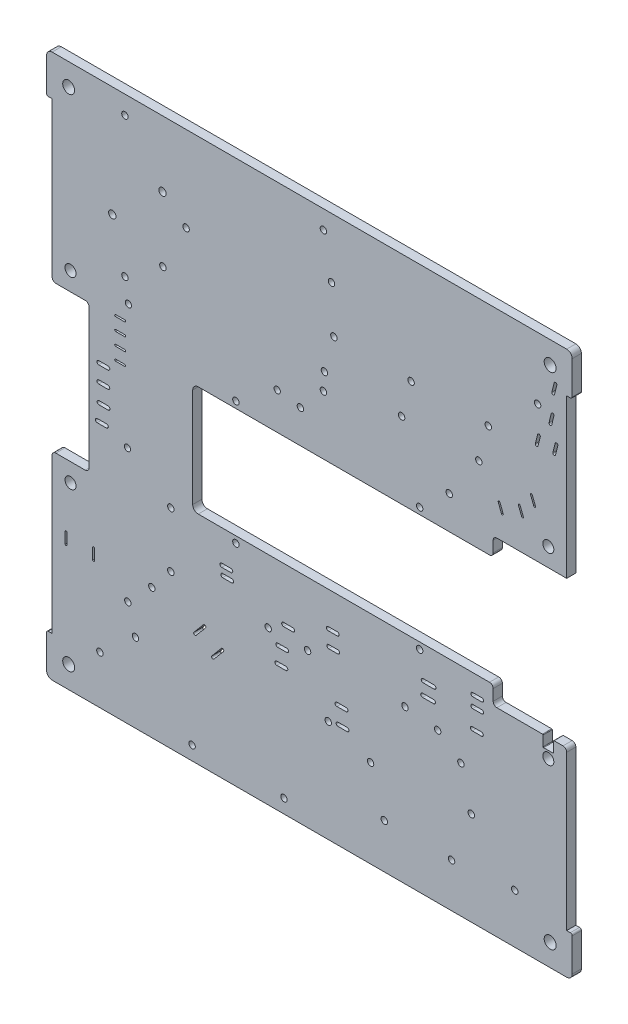
SolidWorks part; units mm, degrees
ref_plane "Front Plane" through (0, 0, 0) normal (0, 0, 1) x (1, 0, 0)
ref_plane "Top Plane" through (0, 0, 0) normal (0, 1, 0) x (1, 0, 0)
ref_plane "Right Plane" through (0, 0, 0) normal (1, 0, 0) x (0, 0, -1)
sketch "Sketch1" plane through (0, 0, 0) normal (0, 0, 1) x (1, 0, 0)
  line L0 (0, -204.8237) -> (0, 174.4772) construction
  line L1 (-143, 174.4772) -> (-143, 126) construction
  line L2 (-199.587, 148) -> (272.3491, 148) construction
  line L3 (-199.587, -148) -> (272.3491, -148) construction
  line L4 (143, 174.4772) -> (143, 127) construction
  line L5 (-199.587, 39.9718) -> (272.3491, 39.9718) construction
  line L6 (-60.5, 29.9898) -> (98, 29.9898)
  line L9 (-63.5, -26.9693) -> (-63.5, 26.9898)
  line L10 (-199.587, 0) -> (272.3491, 0) construction
  line L11 (-60.5, -29.9693) -> (98, -29.9693)
  line L12 (143, -127) -> (143, -204.8237) construction
  line L13 (-199.587, 126) -> (272.3491, 126) construction
  line L14 (-140, 126) -> (-142, 126)
  line L15 (-140, 126) -> (-140, 41.9718)
  line L16 (-143, -127) -> (-143, -145)
  line L17 (-143, -126) -> (-143, -204.8237) construction
  line L18 (-140, -126) -> (-142, -126)
  line L19 (140, -126) -> (142, -126)
  line L20 (140, 126) -> (140, 39.9718)
  line L21 (140, 126) -> (142, 126)
  line L22 (140, -41.9718) -> (140, -126)
  line L23 (143, 127) -> (143, 145)
  line L24 (-132.4113, -74.3153) -> (-132.4113, -80.3153) construction
  line L25 (102, -39.9718) -> (126.8607, -39.9718)
  line L26 (100, -37.9718) -> (100, -31.9693)
  line L27 (100, 37.9718) -> (100, 31.9898)
  line L28 (102, 39.9718) -> (140, 39.9718)
  line L29 (-138, 39.9718) -> (-121.9403, 39.9718)
  line L30 (-119.9403, 37.9718) -> (-119.9403, -38)
  line L31 (-121.9403, -40) -> (-138, -40)
  line L37 (-143, 145) -> (-143, 127)
  line L38 (-140, -148) -> (140, -148)
  line L41 (143, -145) -> (143, -127)
  line L46 (140, 148) -> (-140, 148)
  line L48 (-140, -42) -> (-140, -126)
  line L49 (-131.9113, -74.3153) -> (-131.9113, -80.3153)
  line L50 (-132.9113, -74.3153) -> (-132.9113, -80.3153)
  line L51 (-117.4113, -74.3153) -> (-117.4113, -80.3153) construction
  line L52 (-116.9113, -74.3153) -> (-116.9113, -80.3153)
  line L53 (-117.9113, -74.3153) -> (-117.9113, -80.3153)
  line L66 (-105.4366, 41.087) -> (-100.4366, 41.087) construction
  line L67 (-105.4366, 41.587) -> (-100.4366, 41.587)
  line L68 (-105.4366, 40.587) -> (-100.4366, 40.587)
  line L69 (-105.4366, 34.087) -> (-100.4366, 34.087) construction
  line L70 (-105.4366, 34.587) -> (-100.4366, 34.587)
  line L71 (-105.4366, 33.587) -> (-100.4366, 33.587)
  line L72 (-105.4366, 27.087) -> (-100.4366, 27.087) construction
  line L73 (-105.4366, 27.587) -> (-100.4366, 27.587)
  line L74 (-105.4366, 26.587) -> (-100.4366, 26.587)
  line L75 (-105.4366, 20.087) -> (-100.4366, 20.087) construction
  line L76 (-105.4366, 20.587) -> (-100.4366, 20.587)
  line L77 (-105.4366, 19.587) -> (-100.4366, 19.587)
  line L96 (-57.0801, -81.1454) -> (-62.234, -87.264) construction
  line L97 (-56.5065, -81.6286) -> (-61.6604, -87.7472)
  line L98 (-57.6538, -80.6623) -> (-62.8077, -86.7809)
  line L99 (-52.51, -93.5704) -> (-47.3561, -87.4518) construction
  line L100 (-53.0836, -93.0872) -> (-47.9297, -86.9686)
  line L101 (-51.9364, -94.0536) -> (-46.7825, -87.935)
  line L102 (-199.587, 28.9898) -> (272.3491, 28.9898) construction
  line L103 (-199.587, -28.9693) -> (272.3491, -28.9693) construction
  line L110 (132.8393, -45.8) -> (132.8393, -40.2718)
  line L111 (133.1393, -39.9718) -> (138, -39.9718)
  line L113 (132.5393, -46.1) -> (127.4607, -46.1)
  line L116 (127.1607, -45.8) -> (127.1607, -40.2718)
  line L120 (-199.587, 174.4772) -> (-199.587, -204.8237) construction
  line L121 (-199.587, -204.8237) -> (272.3491, -204.8237) construction
  line L122 (272.3491, -204.8237) -> (272.3491, 174.4772) construction
  line L123 (-199.587, 174.4772) -> (272.3491, 174.4772) construction
  line L157 (-114.6311, 14.3002) -> (-109.6311, 14.3002) construction
  line L158 (-114.6311, 15.3002) -> (-109.6311, 15.3002)
  line L159 (-114.6311, 13.3002) -> (-109.6311, 13.3002)
  line L160 (-114.6311, 5.2497) -> (-109.6311, 5.2497) construction
  line L161 (-114.6311, 6.2497) -> (-109.6311, 6.2497)
  line L162 (-114.6311, 4.2497) -> (-109.6311, 4.2497)
  line L163 (-114.4929, -4.4876) -> (-109.4929, -4.4876) construction
  line L164 (-114.4929, -3.4876) -> (-109.4929, -3.4876)
  line L165 (-114.4929, -5.4876) -> (-109.4929, -5.4876)
  line L166 (-115.4455, -13.4042) -> (-110.4455, -13.4042) construction
  line L167 (-115.4455, -12.4042) -> (-110.4455, -12.4042)
  line L168 (-115.4455, -14.4042) -> (-110.4455, -14.4042)
  line L169 (-14.0645, -58.778) -> (-9.0645, -58.778) construction
  line L170 (-14.0645, -57.778) -> (-9.0645, -57.778)
  line L171 (-14.0645, -59.778) -> (-9.0645, -59.778)
  line L172 (10.4507, -56.9364) -> (15.4507, -56.9364) construction
  line L173 (10.4507, -55.9364) -> (15.4507, -55.9364)
  line L174 (10.4507, -57.9364) -> (15.4507, -57.9364)
  line L175 (-47.7039, -47.6687) -> (-42.7039, -47.6687) construction
  line L176 (-47.7039, -46.6687) -> (-42.7039, -46.6687)
  line L177 (-47.7039, -48.6687) -> (-42.7039, -48.6687)
  line L178 (-47.2405, -52.3025) -> (-42.2405, -52.3025) construction
  line L179 (-47.2405, -51.3025) -> (-42.2405, -51.3025)
  line L180 (-47.2405, -53.3025) -> (-42.2405, -53.3025)
  line L181 (10.219, -48.5955) -> (15.219, -48.5955) construction
  line L182 (10.219, -47.5955) -> (15.219, -47.5955)
  line L183 (10.219, -49.5955) -> (15.219, -49.5955)
  line L184 (-17.3117, -70.106) -> (-12.3117, -70.106) construction
  line L185 (-17.3117, -69.106) -> (-12.3117, -69.106)
  line L186 (-17.3117, -71.106) -> (-12.3117, -71.106)
  line L187 (-17.7732, -78.875) -> (-12.7732, -78.875) construction
  line L188 (-17.7732, -77.875) -> (-12.7732, -77.875)
  line L189 (-17.7732, -79.875) -> (-12.7732, -79.875)
  line L190 (88.8087, -40.369) -> (93.8087, -40.369) construction
  line L191 (88.8087, -39.369) -> (93.8087, -39.369)
  line L192 (88.8087, -41.369) -> (93.8087, -41.369)
  line L193 (88.8087, -46.0036) -> (93.8087, -46.0036) construction
  line L194 (88.8087, -45.0036) -> (93.8087, -45.0036)
  line L195 (88.8087, -47.0036) -> (93.8087, -47.0036)
  line L196 (88.6354, -56.5792) -> (93.6354, -56.5792) construction
  line L197 (88.6354, -55.5792) -> (93.6354, -55.5792)
  line L198 (88.6354, -57.5792) -> (93.6354, -57.5792)
  line L199 (114.1692, 61.6198) -> (115.9798, 56.9591) construction
  line L200 (114.6353, 61.8008) -> (116.4459, 57.1402)
  line L201 (113.7031, 61.4387) -> (115.5138, 56.7781)
  line L202 (103.189, 57.5463) -> (104.9997, 52.8856) construction
  line L203 (103.6551, 57.7273) -> (105.4657, 53.0667)
  line L204 (102.723, 57.3652) -> (104.5336, 52.7046)
  line L205 (120.7594, 69.8959) -> (122.5701, 65.2352) construction
  line L206 (121.2255, 70.077) -> (123.0361, 65.4163)
  line L207 (120.2934, 69.7148) -> (122.104, 65.0542)
  line L244 (61.85, -47.301) -> (67.85, -47.301) construction
  line L245 (61.85, -46.301) -> (67.85, -46.301)
  line L246 (61.85, -48.301) -> (67.85, -48.301)
  line L247 (61.5696, -54.313) -> (67.5696, -54.313) construction
  line L248 (61.5696, -53.313) -> (67.5696, -53.313)
  line L249 (61.5696, -55.313) -> (67.5696, -55.313)
  line L250 (131.1069, 108.3154) -> (132.3521, 113.3154) construction
  line L251 (130.3791, 108.4967) -> (131.6243, 113.4967)
  line L252 (131.8346, 108.1342) -> (133.0799, 113.1342)
  line L259 (132.6394, 123.5259) -> (133.8846, 128.5259) construction
  line L260 (131.9116, 123.7072) -> (133.1569, 128.7072)
  line L261 (133.3672, 123.3447) -> (134.6124, 128.3447)
  line L262 (123.6481, 94.7242) -> (124.8933, 99.7242) construction
  line L263 (122.9203, 94.9054) -> (124.1656, 99.9054)
  line L264 (124.3759, 94.5429) -> (125.6211, 99.5429)
  line L265 (133.2255, 95.2911) -> (134.4707, 100.2911) construction
  line L266 (132.4977, 95.4724) -> (133.743, 100.4724)
  line L267 (133.9533, 95.1099) -> (135.1985, 100.1099)
  line L286 (14.9622, -81.8846) -> (19.9622, -81.8846) construction
  line L287 (14.9622, -80.8846) -> (19.9622, -80.8846)
  line L288 (14.9622, -82.8846) -> (19.9622, -82.8846)
  line L289 (15.4975, -90.9862) -> (20.4975, -90.9862) construction
  line L290 (15.4975, -89.9862) -> (20.4975, -89.9862)
  line L291 (15.4975, -91.9862) -> (20.4975, -91.9862)
  arc A0 (-140, -148) -> (-143, -145) centre (-140, -145) cw
  arc A1 (143, 145) -> (140, 148) centre (140, 145) ccw
  arc A2 (-143, 145) -> (-140, 148) centre (-140, 145) cw
  arc A3 (143, -145) -> (140, -148) centre (140, -145) cw
  circle A4 centre (130, 50) radius 3
  circle A5 centre (130, -50) radius 3
  arc A10 (-63.5, -26.9693) -> (-60.5, -29.9693) centre (-60.5, -26.9693) ccw
  arc A11 (-63.5, 26.9898) -> (-60.5, 29.9898) centre (-60.5, 26.9898) cw
  circle A12 centre (-130, -50) radius 3
  circle A13 centre (-130, 50) radius 3
  circle A14 centre (-131, -136) radius 3.25
  circle A15 centre (131, -136) radius 3.25
  circle A16 centre (131, 136) radius 3.25
  circle A17 centre (-131, 136) radius 3.25
  arc A18 (-142, -126) -> (-143, -127) centre (-142, -127) ccw
  arc A19 (-142, 126) -> (-143, 127) centre (-142, 127) cw
  arc A27 (142, -126) -> (143, -127) centre (142, -127) cw
  arc A28 (142, 126) -> (143, 127) centre (142, 127) ccw
  arc A29 (-131.9113, -74.3153) -> (-132.9113, -74.3153) centre (-132.4113, -74.3153) ccw
  arc A30 (-132.9113, -80.3153) -> (-131.9113, -80.3153) centre (-132.4113, -80.3153) ccw
  circle A31 centre (111.7352, -121.1181) radius 1.75
  circle A32 centre (88.0893, -97) radius 1.75
  arc A33 (102, -39.9718) -> (100, -37.9718) centre (102, -37.9718) cw
  arc A34 (100, 37.9718) -> (102, 39.9718) centre (102, 37.9718) cw
  arc A35 (100, -31.9693) -> (98, -29.9693) centre (98, -31.9693) ccw
  arc A36 (100, 31.9898) -> (98, 29.9898) centre (98, 31.9898) cw
  arc A37 (138, -39.9718) -> (140, -41.9718) centre (138, -41.9718) cw
  arc A38 (-138, -40) -> (-140, -42) centre (-138, -42) ccw
  arc A39 (-138, 39.9718) -> (-140, 41.9718) centre (-138, 41.9718) cw
  arc A40 (-119.9403, -38) -> (-121.9403, -40) centre (-121.9403, -38) cw
  arc A41 (-121.9403, 39.9718) -> (-119.9403, 37.9718) centre (-121.9403, 37.9718) cw
  arc A42 (-116.9113, -74.3153) -> (-117.9113, -74.3153) centre (-117.4113, -74.3153) ccw
  arc A43 (-117.9113, -80.3153) -> (-116.9113, -80.3153) centre (-117.4113, -80.3153) ccw
  circle A46 centre (-107.2747, 87.8236) radius 2
  circle A47 centre (-79.9493, 112.1728) radius 2
  arc A56 (-105.4366, 41.587) -> (-105.4366, 40.587) centre (-105.4366, 41.087) ccw
  arc A57 (-100.4366, 40.587) -> (-100.4366, 41.587) centre (-100.4366, 41.087) ccw
  arc A58 (-105.4366, 34.587) -> (-105.4366, 33.587) centre (-105.4366, 34.087) ccw
  arc A59 (-100.4366, 33.587) -> (-100.4366, 34.587) centre (-100.4366, 34.087) ccw
  arc A60 (-105.4366, 27.587) -> (-105.4366, 26.587) centre (-105.4366, 27.087) ccw
  arc A61 (-100.4366, 26.587) -> (-100.4366, 27.587) centre (-100.4366, 27.087) ccw
  arc A62 (-105.4366, 20.587) -> (-105.4366, 19.587) centre (-105.4366, 20.087) ccw
  arc A63 (-100.4366, 19.587) -> (-100.4366, 20.587) centre (-100.4366, 20.087) ccw
  arc A80 (-56.5065, -81.6286) -> (-57.6538, -80.6623) centre (-57.0801, -81.1454) ccw
  arc A81 (-62.8077, -86.7809) -> (-61.6604, -87.7472) centre (-62.234, -87.264) ccw
  arc A82 (-53.0836, -93.0872) -> (-51.9364, -94.0536) centre (-52.51, -93.5704) ccw
  arc A83 (-46.7825, -87.935) -> (-47.9297, -86.9686) centre (-47.3561, -87.4518) ccw
  circle A84 centre (-40, -33.4898) radius 1.75
  circle A85 centre (60, -33.4898) radius 1.75
  circle A86 centre (-40, 33.5102) radius 1.75
  circle A87 centre (60, 33.5102) radius 1.75
  arc A88 (127.1607, -45.8) -> (127.4607, -46.1) centre (127.4607, -45.8) ccw
  arc A89 (132.5393, -46.1) -> (132.8393, -45.8) centre (132.5393, -45.8) ccw
  arc A90 (132.8393, -40.2718) -> (133.1393, -39.9718) centre (133.1393, -40.2718) cw
  arc A91 (127.1607, -40.2718) -> (126.8607, -39.9718) centre (126.8607, -40.2718) ccw
  arc A128 (-114.6311, 15.3002) -> (-114.6311, 13.3002) centre (-114.6311, 14.3002) ccw
  arc A129 (-109.6311, 13.3002) -> (-109.6311, 15.3002) centre (-109.6311, 14.3002) ccw
  arc A130 (-114.6311, 6.2497) -> (-114.6311, 4.2497) centre (-114.6311, 5.2497) ccw
  arc A131 (-109.6311, 4.2497) -> (-109.6311, 6.2497) centre (-109.6311, 5.2497) ccw
  arc A132 (-114.4929, -3.4876) -> (-114.4929, -5.4876) centre (-114.4929, -4.4876) ccw
  arc A133 (-109.4929, -5.4876) -> (-109.4929, -3.4876) centre (-109.4929, -4.4876) ccw
  arc A134 (-115.4455, -12.4042) -> (-115.4455, -14.4042) centre (-115.4455, -13.4042) ccw
  arc A135 (-110.4455, -14.4042) -> (-110.4455, -12.4042) centre (-110.4455, -13.4042) ccw
  arc A136 (-14.0645, -57.778) -> (-14.0645, -59.778) centre (-14.0645, -58.778) ccw
  arc A137 (-9.0645, -59.778) -> (-9.0645, -57.778) centre (-9.0645, -58.778) ccw
  arc A138 (10.4507, -55.9364) -> (10.4507, -57.9364) centre (10.4507, -56.9364) ccw
  arc A139 (15.4507, -57.9364) -> (15.4507, -55.9364) centre (15.4507, -56.9364) ccw
  arc A140 (-47.7039, -46.6687) -> (-47.7039, -48.6687) centre (-47.7039, -47.6687) ccw
  arc A141 (-42.7039, -48.6687) -> (-42.7039, -46.6687) centre (-42.7039, -47.6687) ccw
  arc A142 (-47.2405, -51.3025) -> (-47.2405, -53.3025) centre (-47.2405, -52.3025) ccw
  arc A143 (-42.2405, -53.3025) -> (-42.2405, -51.3025) centre (-42.2405, -52.3025) ccw
  arc A144 (10.219, -47.5955) -> (10.219, -49.5955) centre (10.219, -48.5955) ccw
  arc A145 (15.219, -49.5955) -> (15.219, -47.5955) centre (15.219, -48.5955) ccw
  arc A146 (-17.3117, -69.106) -> (-17.3117, -71.106) centre (-17.3117, -70.106) ccw
  arc A147 (-12.3117, -71.106) -> (-12.3117, -69.106) centre (-12.3117, -70.106) ccw
  arc A148 (-17.7732, -77.875) -> (-17.7732, -79.875) centre (-17.7732, -78.875) ccw
  arc A149 (-12.7732, -79.875) -> (-12.7732, -77.875) centre (-12.7732, -78.875) ccw
  arc A150 (88.8087, -39.369) -> (88.8087, -41.369) centre (88.8087, -40.369) ccw
  arc A151 (93.8087, -41.369) -> (93.8087, -39.369) centre (93.8087, -40.369) ccw
  arc A152 (88.8087, -45.0036) -> (88.8087, -47.0036) centre (88.8087, -46.0036) ccw
  arc A153 (93.8087, -47.0036) -> (93.8087, -45.0036) centre (93.8087, -46.0036) ccw
  arc A154 (88.6354, -55.5792) -> (88.6354, -57.5792) centre (88.6354, -56.5792) ccw
  arc A155 (93.6354, -57.5792) -> (93.6354, -55.5792) centre (93.6354, -56.5792) ccw
  arc A156 (114.6353, 61.8008) -> (113.7031, 61.4387) centre (114.1692, 61.6198) ccw
  arc A157 (115.5138, 56.7781) -> (116.4459, 57.1402) centre (115.9798, 56.9591) ccw
  arc A158 (103.6551, 57.7273) -> (102.723, 57.3652) centre (103.189, 57.5463) ccw
  arc A159 (104.5336, 52.7046) -> (105.4657, 53.0667) centre (104.9997, 52.8856) ccw
  arc A160 (121.2255, 70.077) -> (120.2934, 69.7148) centre (120.7594, 69.8959) ccw
  arc A161 (122.104, 65.0542) -> (123.0361, 65.4163) centre (122.5701, 65.2352) ccw
  circle A174 centre (-100.3795, 62) radius 1.75
  circle A175 centre (-100.3795, 138) radius 1.75
  circle A176 centre (7.6205, 138) radius 1.75
  circle A179 centre (7.6205, 62) radius 1.75
  arc A191 (61.85, -46.301) -> (61.85, -48.301) centre (61.85, -47.301) ccw
  arc A192 (67.85, -48.301) -> (67.85, -46.301) centre (67.85, -47.301) ccw
  arc A193 (61.5696, -53.313) -> (61.5696, -55.313) centre (61.5696, -54.313) ccw
  arc A194 (67.5696, -55.313) -> (67.5696, -53.313) centre (67.5696, -54.313) ccw
  arc A195 (130.3791, 108.4967) -> (131.8346, 108.1342) centre (131.1069, 108.3154) ccw
  arc A196 (133.0799, 113.1342) -> (131.6243, 113.4967) centre (132.3521, 113.3154) ccw
  arc A201 (131.9116, 123.7072) -> (133.3672, 123.3447) centre (132.6394, 123.5259) ccw
  arc A202 (134.6124, 128.3447) -> (133.1569, 128.7072) centre (133.8846, 128.5259) ccw
  arc A203 (122.9203, 94.9054) -> (124.3759, 94.5429) centre (123.6481, 94.7242) ccw
  arc A204 (125.6211, 99.5429) -> (124.1656, 99.9054) centre (124.8933, 99.7242) ccw
  arc A205 (132.4977, 95.4724) -> (133.9533, 95.1099) centre (133.2255, 95.2911) ccw
  arc A206 (135.1985, 100.1099) -> (133.743, 100.4724) centre (134.4707, 100.2911) ccw
  circle A207 centre (-1, -64.5) radius 1.75
  circle A208 centre (52, -64.5) radius 1.75
  circle A209 centre (-75.4178, -34.5) radius 1.75
  circle A210 centre (-75.4178, -64.5) radius 1.75
  circle A211 centre (-22.4178, -64.5) radius 1.75
  arc A224 (14.9622, -80.8846) -> (14.9622, -82.8846) centre (14.9622, -81.8846) ccw
  arc A225 (19.9622, -82.8846) -> (19.9622, -80.8846) centre (19.9622, -81.8846) ccw
  arc A226 (15.4975, -89.9862) -> (15.4975, -91.9862) centre (15.4975, -90.9862) ccw
  arc A227 (20.4975, -91.9862) -> (20.4975, -89.9862) centre (20.4975, -90.9862) ccw
  circle A228 centre (10.2619, -92.3036) radius 1.75
  circle A229 centre (-98.8, -90.5111) radius 1.75
  circle A230 centre (-94.6354, -105.0746) radius 1.75
  circle A233 centre (-79.7385, 76.9987) radius 1.75
  circle A234 centre (-67.0917, 101.6319) radius 1.75
  circle A237 centre (-99, -18) radius 1.7
  circle A239 centre (-17.5, 50) radius 1.7
  circle A240 centre (-4.9107, 48) radius 1.75
  circle A241 centre (-98.5, 50) radius 1.7
  circle A242 centre (76.0893, 48) radius 1.75
  circle A255 centre (-13.8276, -140.5) radius 1.75
  circle A256 centre (-63.8276, -140.5) radius 1.75
  circle A257 centre (-114.0115, -121.7891) radius 1.75
  circle A258 centre (-85.7443, -77.1553) radius 1.75
  circle A259 centre (33.2709, -100.1136) radius 1.75
  circle A260 centre (82.4129, -75.8537) radius 1.75
  circle A261 centre (69.7695, -66.6758) radius 1.75
  circle A262 centre (124.1732, 114.2153) radius 1.75
  circle A263 centre (92.1743, 71.4677) radius 1.75
  circle A264 centre (97.3301, 90.5) radius 1.75
  circle A265 centre (50.1743, 71.4677) radius 1.75
  circle A266 centre (55.3301, 90.5) radius 1.75
  circle A267 centre (8.1743, 71.4677) radius 1.75
  circle A268 centre (13.3301, 90.5) radius 1.75
  circle A269 centre (12.0222, 115.4507) radius 1.75
  circle A270 centre (40.7563, -123.7307) radius 1.75
  circle A271 centre (77.3546, -124.087) radius 1.75
  point P25 (-143, -148)
  point P28 (143, 148)
  point P31 (-143, 148)
  point P34 (143, -148)
  point P72 (-140, 0)
  point P90 (100, -39.9718)
  point P93 (100, 39.9718)
  point P96 (100, -24.9437)
  point P99 (100, 24.9437)
  point P102 (140, -39.9718)
  point P113 (-140, 39.9718)
  point P118 (-119.9403, 39.9718)
  point P119 (-132.4113, -77.3153)
  point P124 (-117.4113, -77.3153)
  point P167 (-102.9366, 41.087)
  point P174 (-102.9366, 34.087)
  point P183 (-102.9366, 27.087)
  point P190 (-102.9366, 20.087)
  point P245 (-59.6571, -84.2047)
  point P254 (-49.933, -90.5111)
  point P271 (132.8393, -39.9718)
  point P361 (-112.1311, 14.3002)
  point P368 (-112.1311, 5.2497)
  point P377 (-111.9929, -4.4876)
  point P384 (-112.9455, -13.4042)
  point P389 (-11.5645, -58.778)
  point P396 (12.9507, -56.9364)
  point P403 (-45.2039, -47.6687)
  point P410 (-44.7405, -52.3025)
  point P417 (12.719, -48.5955)
  point P424 (-14.8117, -70.106)
  point P431 (-15.2732, -78.875)
  point P438 (91.3087, -40.369)
  point P445 (91.3087, -46.0036)
  point P452 (91.1354, -56.5792)
  point P457 (115.0745, 59.2895)
  point P464 (104.0944, 55.2159)
  point P471 (121.6647, 67.5656)
  point P588 (64.85, -47.301)
  point P595 (64.5696, -54.313)
  point P602 (131.7295, 110.8154)
  point P626 (133.262, 126.0259)
  point P633 (124.2707, 97.2242)
  point P640 (133.8481, 97.7911)
  point P682 (17.4622, -81.8846)
  point P689 (17.9975, -90.9862)
  dimension "D1" = 3
  dimension "D5" = 3
  dimension "D6" = 1
  dimension "D10" = 2
  dimension "D11" = 2
  dimension "D12" = 2
  dimension "D13" = 2
  dimension "D19" = 3.5
  dimension "D20" = 3.5
  dimension "D24" = 4
  dimension "D25" = 4
  dimension "D63" = 3.5
  dimension "D64" = 3.5
  dimension "D65" = 3.5
  dimension "D66" = 3.5
  dimension "D68" = 0.3
  dimension "D76" = 6.5
  dimension "D77" = 6.5
  dimension "D78" = 6.5
  dimension "D79" = 6.5
  dimension "D102" = 3.5
  dimension "D103" = 3.5
  dimension "D104" = 3.5
  dimension "D105" = 3.5
  dimension "D115" = 3.5
  dimension "D116" = 3.5
  dimension "D117" = 3.5
  dimension "D118" = 3.5
  dimension "D119" = 3.5
  dimension "D128" = 3.5
  dimension "D131" = 3.4
  dimension "D132" = 3.4
  dimension "D133" = 3.4
  dimension "D7" = 3
  dimension "D8" = 1
  dimension "D9" = 40
  dimension "D14" = 1
  dimension "D15" = 6
  dimension "D16" = 6
  dimension "D17" = 1
  dimension "D18" = 15
  dimension "D34" = 1
  dimension "D35" = 5
  dimension "D36" = 1
  dimension "D37" = 5
  dimension "D38" = 6
  dimension "D39" = 1
  dimension "D40" = 5
  dimension "D41" = 6
  dimension "D42" = 1
  dimension "D43" = 5
  dimension "D44" = 6
  dimension "D56" = 5
  dimension "D58" = 1.5
  dimension "D59" = 8
  dimension "D60" = 8
  dimension "D61" = 1.5
  dimension "D62" = 10
  dimension "D67" = 1
  dimension "D70" = 76.5
  dimension "D85" = 5
  dimension "D86" = 2
  dimension "D87" = 5
  dimension "D88" = 5
  dimension "D89" = 5
  dimension "D90" = 5
  dimension "D91" = 5
  dimension "D92" = 5
  dimension "D93" = 5
  dimension "D94" = 5
  dimension "D95" = 5
  dimension "D96" = 5
  dimension "D97" = 5
  dimension "D98" = 5
  dimension "D99" = 5
  dimension "D100" = 5
  dimension "D101" = 5
  dimension "D112" = 5
  dimension "D113" = 5
  dimension "D114" = 5
  dimension "D126" = 5
  dimension "D127" = 5
extrude "Boss-Extrude1" add sketch "Sketch1" along normal blind 5
